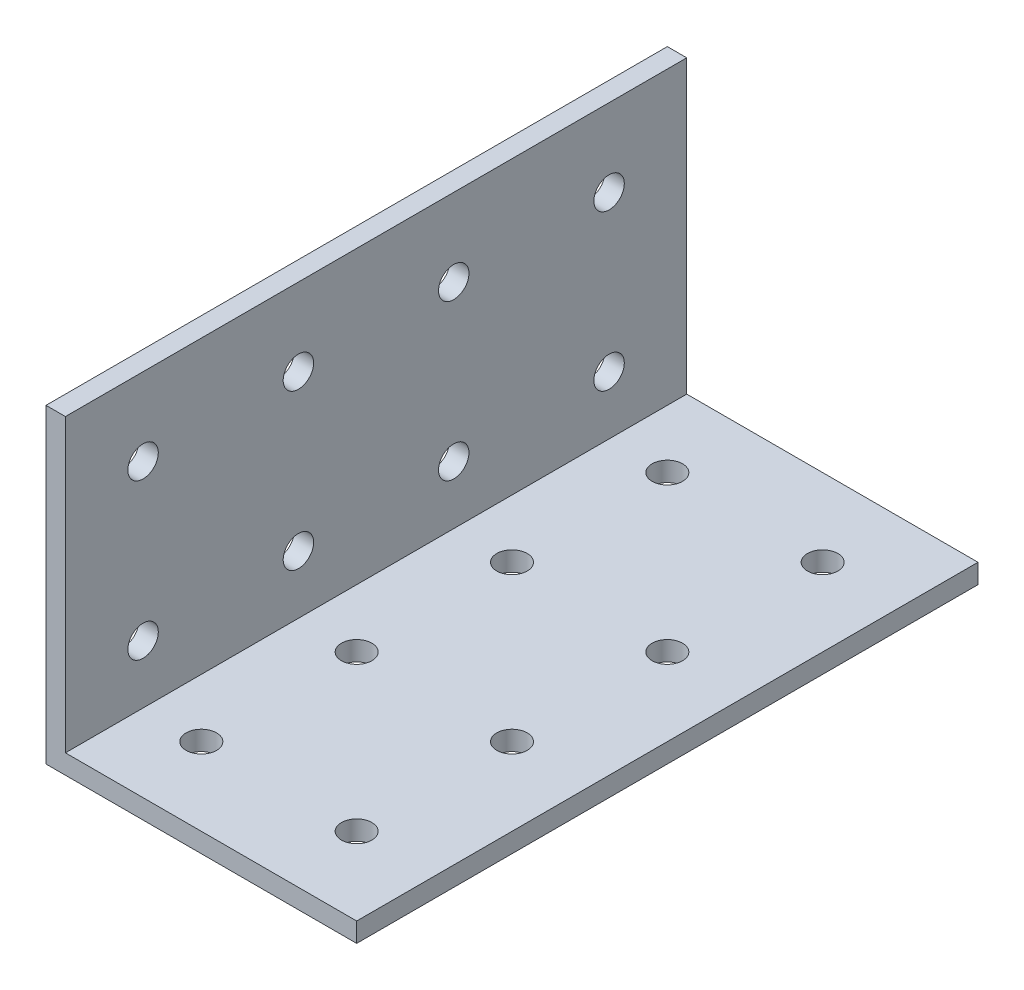
SolidWorks part; units mm, degrees
material "6061-T6 (SS)"
ref_plane "Front Plane" through (0, 0, 0) normal (0, 0, 1) x (1, 0, 0)
ref_plane "Top Plane" through (0, 0, 0) normal (0, 1, 0) x (1, 0, 0)
ref_plane "Right Plane" through (0, 0, 0) normal (1, 0, 0) x (0, 0, -1)
sketch "Sketch1" plane through (0, 0, 0) normal (0, 0, 1) x (1, 0, 0)
  line L1 (0, 0) -> (3.175, 0)
  line L2 (0, 0) -> (0, 50.8)
  line L3 (0, 50.8) -> (3.175, 50.8)
  line L4 (3.175, 0) -> (3.175, 50.8)
  line L5 (0, 0) -> (50.8, 0)
  line L6 (0, 0) -> (0, 3.175)
  line L7 (0, 3.175) -> (50.8, 3.175)
  line L8 (50.8, 0) -> (50.8, 3.175)
  dimension "D1" = 3.175
  dimension "D2" = 50.8
  dimension "D3" = 50.8
  dimension "D4" = 3.175
extrude "Boss-Extrude1" add sketch "Sketch1" along normal blind 101.6 contours L2 L7 L4 L3 | L7 L2 L1 L4 | L5 L8 L7 L4
sketch "Sketch2" plane through (0, 3.175, 0) normal (0, 1, 0) x (1, 0, 0)
  line L0 (3.175, 0) -> (50.8, 0) construction
  line L1 (50.8, -101.6) -> (50.8, 0) construction
  circle A0 centre (38.1, -12.7) radius 2.4892
  circle A1 centre (12.7, -12.7) radius 2.4892
  circle A2 centre (12.7, -38.1) radius 2.4892
  circle A3 centre (12.7, -63.5) radius 2.4892
  circle A4 centre (12.7, -88.9) radius 2.4892
  circle A5 centre (38.1, -38.1) radius 2.4892
  circle A6 centre (38.1, -63.5) radius 2.4892
  circle A7 centre (38.1, -88.9) radius 2.4892
  dimension "D1" = 4.9784
  dimension "D2" = 12.7
  dimension "D3" = 12.7
  dimension "D6" = 25.4
  dimension "D7" = 25.4
  dimension "D4" = 2
  dimension "D5" = 4
extrude "Cut-Extrude1" cut sketch "Sketch2" against normal blind 101.6
sketch "Sketch3" plane through (3.175, 0, 0) normal (1, 0, 0) x (0, 0, -1)
  line L0 (-101.6, 50.8) -> (0, 50.8) construction
  line L1 (-101.6, 3.175) -> (-101.6, 50.8) construction
  circle A0 centre (-88.9, 38.1) radius 2.4892
  circle A1 centre (-63.5, 38.1) radius 2.4892
  circle A2 centre (-38.1, 38.1) radius 2.4892
  circle A3 centre (-12.7, 38.1) radius 2.4892
  circle A4 centre (-63.5, 12.7) radius 2.4892
  circle A5 centre (-38.1, 12.7) radius 2.4892
  circle A6 centre (-12.7, 12.7) radius 2.4892
  circle A7 centre (-88.9, 12.7) radius 2.4892
  dimension "D1" = 4.9784
  dimension "D2" = 12.7
  dimension "D6" = 25.4
  dimension "D7" = 25.4
  dimension "D3" = 12.7
  dimension "D4" = 4
  dimension "D5" = 2
extrude "Cut-Extrude2" cut sketch "Sketch3" against normal blind 101.6
